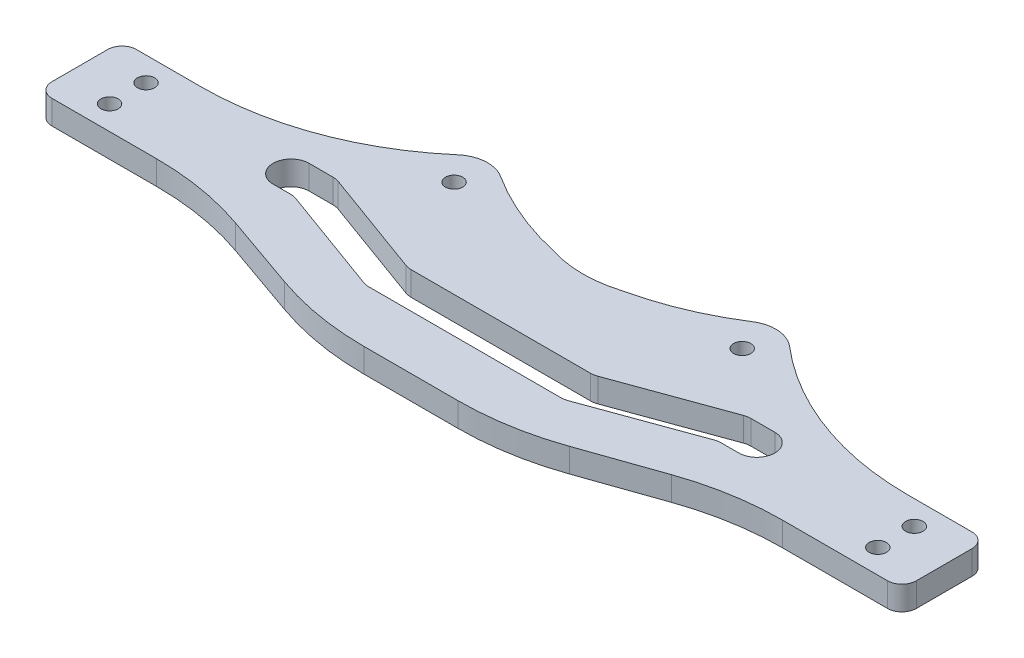
SolidWorks part; units mm, degrees
ref_plane "Front Plane" through (0, 0, 0) normal (0, 0, 1) x (1, 0, 0)
ref_plane "Top Plane" through (0, 0, 0) normal (0, 1, 0) x (1, 0, 0)
ref_plane "Right Plane" through (0, 0, 0) normal (1, 0, 0) x (0, 0, -1)
sketch "Sketch1" plane through (0, 0, 0) normal (0, 1, 0) x (1, 0, 0)
  line L0 (0, 0) -> (-24.2803, 0) construction
  line L1 (-114.2815, -3.4925) -> (-69.8315, -3.4925)
  line L2 (-114.2815, -3.4925) -> (-114.2815, 18.8595)
  line L3 (-114.2815, 18.8595) -> (-46.99, 18.8595)
  line L4 (114.3185, -3.4925) -> (114.3185, 18.8595)
  line L5 (-69.8315, -3.4925) -> (-25.4, -19.05)
  line L6 (-25.4, -19.05) -> (25.4, -19.05)
  line L7 (25.4, -4.7625) -> (-25.4, -4.7625)
  line L8 (23.7205, 4.7625) -> (-23.7205, 4.7625)
  line L9 (-26.4522, 0.383) -> (-54.1831, 10.4762) construction
  line L10 (-27.0289, -4.4753) -> (-55.2859, 5.8094)
  line L11 (-25.3494, 5.0497) -> (-53.6064, 15.3344)
  line L12 (-56.3549, 10.8591) -> (-61.5852, 10.8591) construction
  line L13 (-56.9148, 6.0966) -> (-61.5852, 6.0966)
  line L14 (-55.2352, 15.6216) -> (-61.5852, 15.6216)
  line L15 (0, 4.7625) -> (0, -4.7625) construction
  line L16 (-61.5852, 15.6216) -> (-61.5852, 6.0966) construction
  line L17 (55.2352, 15.6216) -> (61.5852, 15.6216)
  line L18 (56.9148, 6.0966) -> (61.5852, 6.0966)
  line L19 (25.3494, 5.0497) -> (53.6064, 15.3344)
  line L20 (27.0289, -4.4753) -> (55.2859, 5.8094)
  line L21 (-46.99, 18.8595) -> (-46.99, 30.48)
  line L22 (-29.21, 30.48) -> (-29.21, 27.94)
  line L23 (29.21, 30.48) -> (29.21, 27.94)
  line L24 (46.99, 18.8595) -> (46.99, 30.48)
  line L25 (9.322, 27.94) -> (29.21, 27.94)
  line L26 (-29.21, 27.94) -> (-9.322, 27.94)
  line L27 (46.99, 18.8595) -> (114.3185, 18.8595)
  line L28 (0, -19.05) -> (0, 0) construction
  line L29 (69.8315, -3.4925) -> (25.4, -19.05)
  line L30 (69.8315, -3.4925) -> (114.3185, -3.4925)
  arc A1 (-27.0289, -4.4753) -> (-25.4, -4.7625) centre (-25.4, 0) ccw
  arc A2 (-27.0289, -4.4753) -> (-25.4, -4.7625) centre (-25.4, 0) ccw
  arc A3 (-53.6064, 15.3344) -> (-55.2352, 15.6216) centre (-55.2352, 10.8591) ccw
  arc A4 (-53.6064, 15.3344) -> (-55.2352, 15.6216) centre (-55.2352, 10.8591) ccw
  arc A5 (-61.5852, 15.6216) -> (-61.5852, 6.0966) centre (-61.5852, 10.8591) ccw
  arc A6 (-55.2859, 5.8094) -> (-56.9148, 6.0966) centre (-56.9148, 1.3341) ccw
  arc A7 (-23.7205, 4.7625) -> (-25.3494, 5.0497) centre (-23.7205, 9.525) cw
  arc A8 (53.6064, 15.3344) -> (55.2352, 15.6216) centre (55.2352, 10.8591) cw
  arc A9 (61.5852, 15.6216) -> (61.5852, 6.0966) centre (61.5852, 10.8591) cw
  arc A10 (55.2859, 5.8094) -> (56.9148, 6.0966) centre (56.9148, 1.3341) cw
  arc A11 (23.7205, 4.7625) -> (25.3494, 5.0497) centre (23.7205, 9.525) ccw
  arc A12 (27.0289, -4.4753) -> (25.4, -4.7625) centre (25.4, 0) cw
  circle A13 centre (-101.5815, 12.5095) radius 2.286
  circle A14 centre (-101.5815, 2.8575) radius 2.286
  circle A15 centre (101.5815, 12.5095) radius 2.286
  circle A16 centre (101.5815, 2.8575) radius 2.286
  circle A17 centre (-38.1, 30.48) radius 2.286
  circle A18 centre (38.1, 30.48) radius 2.286
  arc A19 (-29.21, 30.48) -> (-46.99, 30.48) centre (-38.1, 30.48) ccw
  arc A20 (-9.322, 27.94) -> (9.322, 27.94) centre (0, 56.9595) ccw
  arc A21 (29.21, 30.48) -> (46.99, 30.48) centre (38.1, 30.48) cw
  arc A22 (-54.1831, 10.4762) -> (-56.3549, 10.8591) centre (-56.3549, 4.5091) ccw construction
  arc A23 (-26.4522, 0.383) -> (-24.2803, 0) centre (-24.2803, 6.35) ccw construction
  point P0 (0, 0)
  point P77 (0, -8.5725)
  dimension "D3" = 9.525
  dimension "D4" = 12.7
  dimension "D10" = 4.572
  dimension "D16" = 4.572
  dimension "D17" = 60.96
  dimension "D19" = 8.89
  dimension "D20" = 6.35
  dimension "D21" = 6.35
  dimension "D2" = 22.352
  dimension "D5" = 25.4
  dimension "D6" = 160
  dimension "D7" = 160
  dimension "D8" = 31.75
  dimension "D9" = 6.35
  dimension "D11" = 6.35
  dimension "D12" = 6.35
  dimension "D13" = 1.27
  dimension "D14" = 38.1
  dimension "D15" = 11.6205
  dimension "D18" = 38.1
  dimension "D22" = 114.2815
  dimension "D23" = 2.54
  dimension "D24" = 19.05
  dimension "D25" = 44.45
  dimension "D26" = 50.8
  dimension "D27" = 228.6
extrude "Boss-Extrude1" add sketch "Sketch1" along normal blind 6.35 contours A21 L23 L25 A20 L26 L22 A19 L21 L3 L2 L1 L5 L6 L29 L30 L4 L27 L24 A16 L20 A12 L7 A1 L10 A6 L13 A5 L14 A3 L11 A7 L8 A11 L19 A8 L17 A9 L18 A10 A13 A14 A15 A17 A18
fillet "Fillet2" radius 3.81 6 edges at (114.3185, 3.175, -18.8595) (-114.2815, 3.175, 3.4925) (-114.2815, 3.175, -18.8595) (114.3185, 3.175, 3.4925) (9.322, 3.175, -27.94) (-9.322, 3.175, -27.94)
fillet "Fillet3" radius 76.2 8 edges at (-46.99, 3.175, -18.8595) (-29.21, 3.175, -27.94) (29.21, 3.175, -27.94) (46.99, 3.175, -18.8595) (69.8315, 3.175, 3.4925) (25.4, 3.175, 19.05) (-25.4, 3.175, 19.05) (-69.8315, 3.175, 3.4925)
